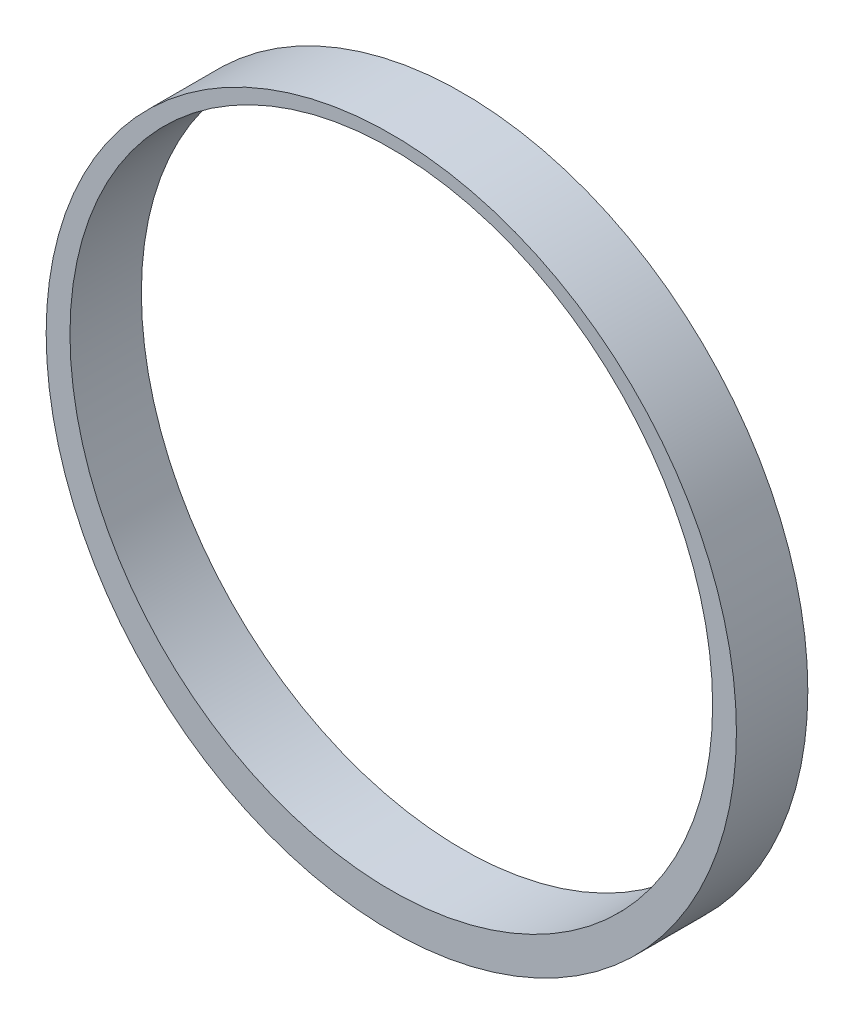
SolidWorks part; units mm, degrees
ref_plane "Front Plane" through (0, 0, 0) normal (0, 0, 1) x (1, 0, 0)
ref_plane "Top Plane" through (0, 0, 0) normal (0, 1, 0) x (1, 0, 0)
ref_plane "Right Plane" through (0, 0, 0) normal (1, 0, 0) x (0, 0, -1)
sketch "Sketch1" plane through (0, 0, 0) normal (0, 0, 1) x (1, 0, 0)
  circle A0 centre (0, -1.8966) radius 58
extrude "Boss-Extrude2" add sketch "Sketch1" along normal blind 12
sketch "Sketch5" plane through (0, 0, 0) normal (0, 0, 1) x (1, 0, 0)
  circle A0 centre (0, 0) radius 54
extrude "Cut-Extrude1" cut sketch "Sketch5" along normal blind 23 contours A0
